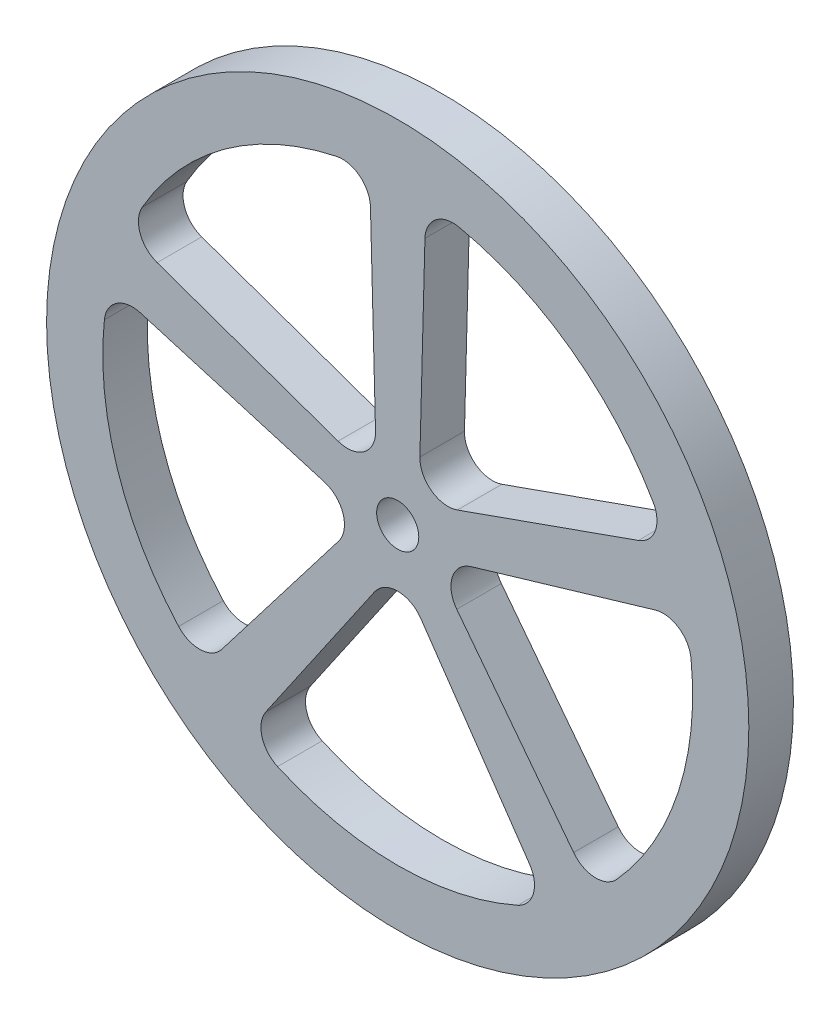
SolidWorks part; units mm, degrees
material "6061 Alloy"
ref_plane "Front Plane" through (0, 0, 0) normal (0, 0, 1) x (1, 0, 0)
ref_plane "Top Plane" through (0, 0, 0) normal (0, 1, 0) x (1, 0, 0)
ref_plane "Right Plane" through (0, 0, 0) normal (1, 0, 0) x (0, 0, -1)
sketch "Sketch1" plane through (0, 0, 0) normal (0, 0, 1) x (1, 0, 0)
  circle A0 centre (0, 0) radius 25
  circle A1 centre (0, 0) radius 21
  circle A2 centre (0, 0) radius 2.5
  circle A3 centre (0, 0) radius 1.5
  dimension "D1" = 50
  dimension "D2" = 4
  dimension "D3" = 5
  dimension "D4" = 3
extrude "Boss-Extrude1" add sketch "Sketch1" along normal blind 3.175 contours A0 A1 | A2 A3
sketch "Sketch2" plane through (0, 0, 0) normal (0, 0, 1) x (1, 0, 0)
  line L0 (0, 0) -> (0, 25) construction
  line L1 (1.5, 2) -> (2, 20.9045)
  line L2 (-1.5, 2) -> (-2, 20.9045)
  circle A1 centre (0, 0) radius 25 construction
  circle A2 centre (0, 0) radius 2.5 construction
  circle A3 centre (0, 0) radius 21 construction
  arc A4 (2, 20.9045) -> (-2, 20.9045) centre (0, 0) ccw
  arc A5 (-1.5, 2) -> (1.5, 2) centre (0, 0) cw
  dimension "D1" = 4
  dimension "D2" = 3
extrude "Boss-Extrude2" add sketch "Sketch2" along normal up to surface (3.175 mm away) contours A5 L0 A4 L2 | L0 A5 L1 A4 up to face at (21, 0, 3.175)
pattern_circular "CirPattern1" count 5 over 360 about axis through (0, 0, 0) along (0, 0, 1) of "Boss-Extrude2"
fillet "Fillet1" radius 2 5 edges at (-1.5018, 2.067, 1.5875) (-2.4299, -0.7895, 1.5875) (0, -2.555, 1.5875) (2.4299, -0.7895, 1.5875) (1.5018, 2.067, 1.5875)
fillet "Fillet2" radius 2 10 edges at (-20.4994, 4.5577, 1.5875) (2, 20.9045, 1.5875) (-19.2634, 8.362, 1.5875) (-2, 20.9045, 1.5875) (20.4994, 4.5577, 1.5875) (19.2634, 8.362, 1.5875) (10.6693, -18.0877, 1.5875) (13.9054, -15.7366, 1.5875) (-10.6693, -18.0877, 1.5875) (-13.9054, -15.7366, 1.5875)
ref_plane "Plane1" through (0, -25, 0) normal (0, -1, 0) x (-1, 0, 0)
ref_plane "Plane2" through (0, -24.9, 0) normal (0, -1, 0) x (-1, 0, 0)
sketch "Sketch5" plane through (0, -24.9, 0) normal (0, -1, 0) x (-1, 0, 0)
  line L0 (8.5527, 0) -> (-8.5527, 0) construction
  line L1 (-1.3611, 0) -> (1.3611, 0)
  line L2 (-1.3611, 0) -> (-1.3611, -3.175)
  line L3 (-1.3611, -3.175) -> (1.3611, -3.175)
  line L4 (1.3611, 0) -> (1.3611, -3.175)
  line L5 (-25, -3.175) -> (25, -3.175) construction
  line L6 (0, -3.175) -> (0, 0) construction
split line "Split Line1" [suppressed]
